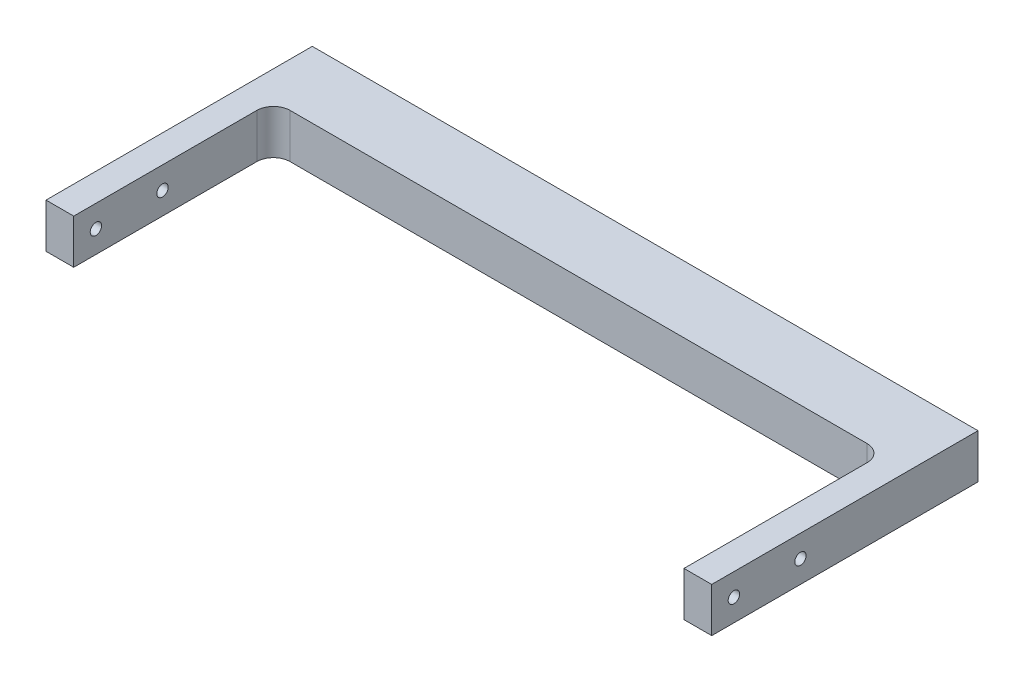
SolidWorks part; units mm, degrees
ref_plane "Front" through (0, 0, 0) normal (0, 0, 1) x (1, 0, 0)
ref_plane "Top" through (0, 0, 0) normal (0, 1, 0) x (1, 0, 0)
ref_plane "Right" through (0, 0, 0) normal (1, 0, 0) x (0, 0, -1)
sketch "Sketch1" plane through (0, 0, 0) normal (0, 1, 0) x (1, 0, 0)
  line L0 (174.625, -152.4) -> (190.5, -152.4)
  line L1 (-190.5, 0) -> (190.5, 0)
  line L2 (-190.5, 0) -> (-190.5, -152.4)
  line L3 (-190.5, -152.4) -> (-174.625, -152.4)
  line L4 (190.5, 0) -> (190.5, -152.4)
  line L6 (-174.625, -152.4) -> (-174.625, -38.1)
  line L7 (-174.625, -38.1) -> (174.625, -38.1)
  line L8 (174.625, -152.4) -> (174.625, -38.1)
  dimension "D1" = 381
  dimension "D2" = 152.4
  dimension "D3" = 114.3
  dimension "D4" = 15.875
  dimension "D5" = 349.25
extrude "Extrude1" add sketch "Sketch1" along normal blind 25.4
fillet "Fillet1" radius 9.525 2 edges at (174.625, 12.7, 38.1) (-174.625, 12.7, 38.1)
hole_wizard "5/16-18 Tapped Hole1" positions "Sketch3" profile "Sketch2" tap size "5/16-18" standard "Ansi Inch"
sketch "Sketch3" plane through (190.5, 0, 0) normal (1, 0, 0) x (0, 0, -1)
  line L0 (-152.4, 0) -> (0, 0) construction
  line L1 (0, 25.4) -> (0, 0) construction
  point P0 (-139.7, 12.7)
  point P1 (-101.6, 12.7)
  dimension "D1" = 12.7
  dimension "D2" = 38.1
  dimension "D3" = 101.6
cosmetic thread "Hole Thread1" parameters "D2"=7.9375
cosmetic thread "Hole Thread2" parameters "D2"=7.9375
sketch "Sketch2" plane through (190.5, 12.7, 139.7) normal (0, 1, 0) x (0, 0, -1)
  line L0 (0, 0) -> (0, 15.875)
  line L1 (0, 15.875) -> (3.2639, 15.875)
  line L2 (3.2639, 15.875) -> (3.2639, 0)
  line L5 (3.2639, 0) -> (0, 0)
  line L11 (0, -6.35) -> (0, 107.95) construction
  dimension "Thru Tap Drill Dia." = 6.5278
  dimension "Thru Tap Drill Depth" = 15.875
hole_wizard "5/16-18 Tapped Hole2" positions "Sketch5" profile "Sketch4" tap size "5/16-18" standard "Ansi Inch" end condition up to next
sketch "Sketch5" plane through (-190.5, 0, 0) normal (-1, 0, 0) x (0, 0, 1)
  point P1 (101.6, 12.7)
  point P4 (139.7, 12.7)
cosmetic thread "Hole Thread3" parameters "D2"=7.9375
sketch "Sketch4" plane through (-190.5, 12.7, 101.6) normal (0, 1, 0) x (0, 0, 1)
  line L0 (0, 0) -> (0, 15.875)
  line L1 (0, 15.875) -> (3.2639, 15.875)
  line L2 (3.2639, 15.875) -> (3.2639, 0)
  line L5 (3.2639, 0) -> (0, 0)
  line L11 (0, -6.35) -> (0, 107.95) construction
  dimension "Thru Tap Drill Dia." = 6.5278
  dimension "Thru Tap Drill Depth" = 15.875
cosmetic thread "Hole Thread5" parameters "D2"=7.9375
